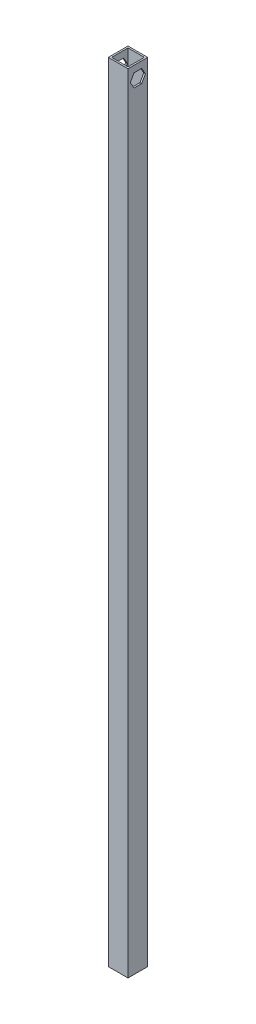
SolidWorks part; units mm, degrees
ref_plane "Front Plane" through (0, 0, 0) normal (0, 0, 1) x (1, 0, 0)
ref_plane "Top Plane" through (0, 0, 0) normal (0, 1, 0) x (1, 0, 0)
ref_plane "Right Plane" through (0, 0, 0) normal (1, 0, 0) x (0, 0, -1)
sketch "Sketch1" plane through (0, 0, 0) normal (0, 1, 0) x (1, 0, 0)
  line L0 (3.175, 34.925) -> (34.925, 34.925)
  line L1 (0, 0) -> (38.1, 0)
  line L2 (0, 0) -> (0, 38.1)
  line L3 (0, 38.1) -> (38.1, 38.1)
  line L4 (38.1, 0) -> (38.1, 38.1)
  line L5 (34.925, 3.175) -> (34.925, 34.925)
  line L6 (3.175, 3.175) -> (34.925, 3.175)
  line L7 (3.175, 3.175) -> (3.175, 34.925)
  dimension "D1" = 38.1
  dimension "D2" = 38.1
  dimension "D3" = 3.175
extrude "Boss-Extrude1" add sketch "Sketch1" along normal blind 1524
sketch "Sketch2" plane through (38.1, 0, 0) normal (1, 0, 0) x (0, 0, -1)
  line L0 (0, 1524) -> (38.1, 1524) construction
  line L1 (33.7147, 1498.6) -> (26.3823, 1511.3)
  line L2 (26.3823, 1511.3) -> (11.7177, 1511.3)
  line L3 (11.7177, 1511.3) -> (4.3853, 1498.6)
  line L4 (4.3853, 1498.6) -> (11.7177, 1485.9)
  line L5 (11.7177, 1485.9) -> (26.3823, 1485.9)
  line L6 (26.3823, 1485.9) -> (33.7147, 1498.6)
  line L7 (38.1, 1524) -> (38.1, 0) construction
  circle A0 centre (19.05, 1498.6) radius 12.7 construction
  dimension "D1" = 25.4
  dimension "D2" = 19.05
extrude "Cut-Extrude1" cut sketch "Sketch2" against normal blind 38.1
